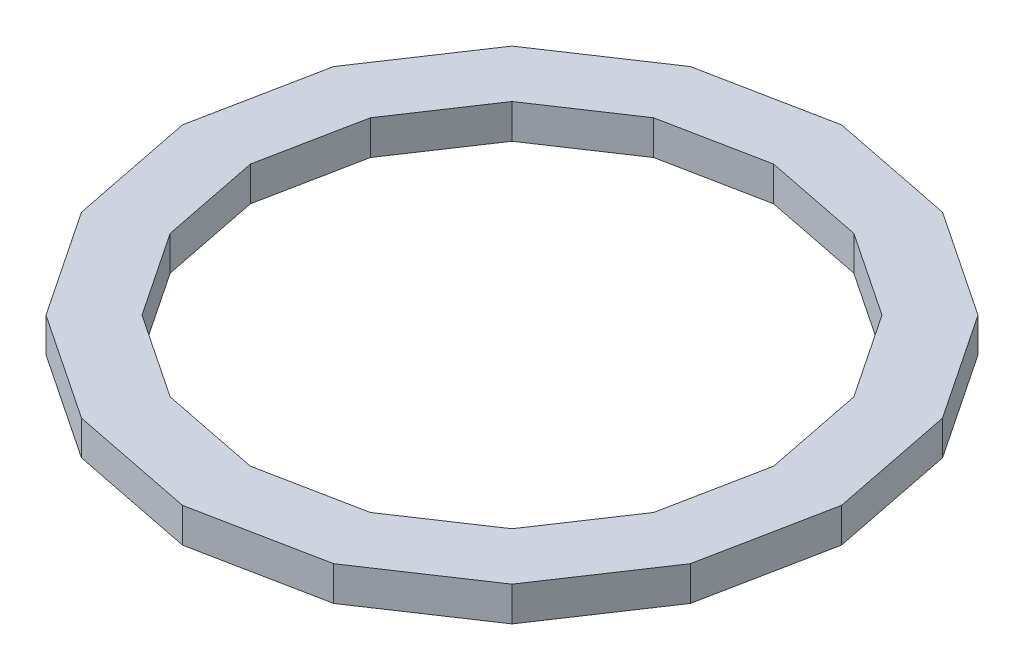
SolidWorks part; units mm, degrees
ref_plane "Front Plane" through (0, 0, 0) normal (0, 0, 1) x (1, 0, 0)
ref_plane "Top Plane" through (0, 0, 0) normal (0, 1, 0) x (1, 0, 0)
ref_plane "Right Plane" through (0, 0, 0) normal (1, 0, 0) x (0, 0, -1)
sketch "Sketch1" plane through (0, 0, 0) normal (0, 1, 0) x (1, 0, 0)
  line L1 (182.2745, 0) -> (168.3997, 69.7534)
  line L2 (168.3997, 69.7534) -> (128.8876, 128.8876)
  line L3 (128.8876, 128.8876) -> (69.7534, 168.3997)
  line L4 (69.7534, 168.3997) -> (0, 182.2745)
  line L5 (0, 182.2745) -> (-69.7534, 168.3997)
  line L6 (-69.7534, 168.3997) -> (-128.8876, 128.8876)
  line L7 (-128.8876, 128.8876) -> (-168.3997, 69.7534)
  line L8 (-168.3997, 69.7534) -> (-182.2745, 0)
  line L9 (-182.2745, 0) -> (-168.3997, -69.7534)
  line L10 (-168.3997, -69.7534) -> (-128.8876, -128.8876)
  line L11 (-128.8876, -128.8876) -> (-69.7534, -168.3997)
  line L12 (-69.7534, -168.3997) -> (0, -182.2745)
  line L13 (0, -182.2745) -> (69.7534, -168.3997)
  line L14 (69.7534, -168.3997) -> (128.8876, -128.8876)
  line L15 (128.8876, -128.8876) -> (168.3997, -69.7534)
  line L16 (168.3997, -69.7534) -> (182.2745, 0)
  line L17 (144.723, 0) -> (133.7066, 55.3831)
  line L18 (133.7066, 55.3831) -> (102.3346, 102.3346)
  line L19 (102.3346, 102.3346) -> (55.3831, 133.7066)
  line L20 (55.3831, 133.7066) -> (0, 144.723)
  line L21 (0, 144.723) -> (-55.3831, 133.7066)
  line L22 (-55.3831, 133.7066) -> (-102.3346, 102.3346)
  line L23 (-102.3346, 102.3346) -> (-133.7066, 55.3831)
  line L24 (-133.7066, 55.3831) -> (-144.723, 0)
  line L25 (-144.723, 0) -> (-133.7066, -55.3831)
  line L26 (-133.7066, -55.3831) -> (-102.3346, -102.3346)
  line L27 (-102.3346, -102.3346) -> (-55.3831, -133.7066)
  line L28 (-55.3831, -133.7066) -> (0, -144.723)
  line L29 (0, -144.723) -> (55.3831, -133.7066)
  line L30 (55.3831, -133.7066) -> (102.3346, -102.3346)
  line L31 (102.3346, -102.3346) -> (133.7066, -55.3831)
  line L32 (133.7066, -55.3831) -> (144.723, 0)
  circle A0 centre (0, 0) radius 178.7722 construction
  circle A1 centre (0, 0) radius 141.9422 construction
  dimension "D1" = 36.83
  dimension "D2" = 71.12
extrude "Boss-Extrude1" add sketch "Sketch1" along normal blind 19.05
